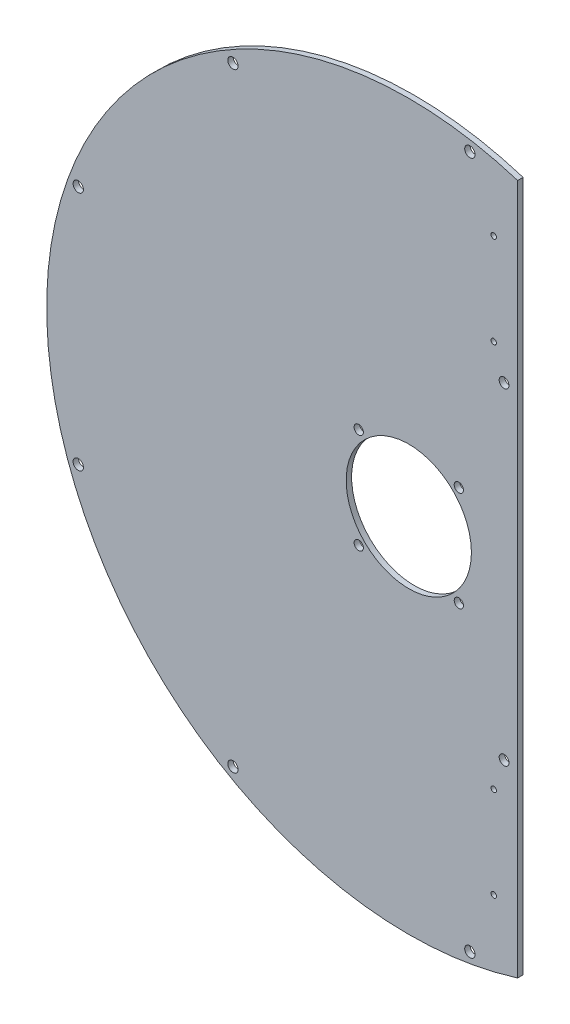
SolidWorks part; units mm, degrees
material "1.4301 (X5CrNi18-10)"
ref_plane "Ebene 1" through (0, 0, 0) normal (0, 0, 1) x (1, 0, 0)
ref_plane "Ebene 2" through (0, 0, 0) normal (0, 1, 0) x (1, 0, 0)
ref_plane "Ebene 3" through (0, 0, 0) normal (1, 0, 0) x (0, 0, -1)
sketch "Skizze1" plane through (0, 0, 0) normal (0, 0, 1) x (1, 0, 0)
  line L0 (100, 317.1061) -> (100, -317.1061)
  line L1 (0, 0) -> (0, 365.1695) construction
  line L2 (0, 0) -> (63.3988, 359.5525) construction
  line L3 (0, 0) -> (56.0884, 318.0929) construction
  line L4 (0, 0) -> (-194.2815, 336.5054) construction
  line L5 (0, 0) -> (68.873, -390.5983) construction
  arc A0 (100, 317.1061) -> (100, -317.1061) centre (0, 0) ccw
  circle A1 centre (56.0884, 318.0929) radius 4.75
  circle A2 centre (323, 0) radius 4.75 [skipped]
  circle A3 centre (247.4324, -207.6204) radius 4.75 [skipped]
  arc A4 (71.0884, 315.0801) -> (71.0884, -315.0801) centre (0, 0) ccw construction
  circle A5 centre (56.0884, -318.0929) radius 4.75
  circle A6 centre (-161.5, -279.7262) radius 4.75
  circle A7 centre (-303.5207, -110.4725) radius 4.75
  circle A8 centre (-303.5207, 110.4725) radius 4.75
  circle A9 centre (-161.5, 279.7262) radius 4.75
  circle A10 centre (247.4324, 207.6204) radius 4.75 [skipped]
  dimension "D1" = 665
  dimension "D3" = 9.5
  dimension "D8" = 646
  dimension "D6" = 200
  dimension "D2" = 100
  dimension "D4" = 40
  dimension "D5" = 10
  dimension "D7" = 323
  dimension "D9" = 15
extrude "Linear austragen1" add sketch "Skizze1" along normal blind 5
sketch "Skizze4" plane through (0, 0, 5) normal (0, 0, 1) x (1, 0, 0)
  line L1 (100, -317.1061) -> (100, 317.1061)
  line L2 (100, -317.1061) -> (100, 317.1061)
  arc A1 (100, 317.1061) -> (100, -317.1061) centre (0, 0) ccw
  arc A2 (100, 317.1061) -> (100, -317.1061) centre (0, 0) ccw
  dimension "D1" = 0
sketch "Skizze10" plane through (0, 0, 5) normal (0, 0, 1) x (1, 0, 0)
  circle A0 centre (0, 0) radius 57.5
  dimension "D1" = 115
extrude "Schnitt-Linear austragen3" cut sketch "Skizze10" against normal through all
sketch "Skizze15" plane through (0, 0, 5) normal (0, 0, 1) x (1, 0, 0)
  line L0 (0, 82.1456) -> (0, -86.7126) construction
  line L1 (-72.4332, 0) -> (68.4613, 0) construction
  line L2 (0, 0) -> (-71.1009, 71.1009) construction
  line L3 (0, 0) -> (71.1009, 71.1009) construction
  line L4 (0, 0) -> (71.1009, -71.1009) construction
  line L5 (0, 0) -> (-71.1009, -71.1009) construction
  circle A0 centre (-45.9619, 45.9619) radius 4.25
  circle A1 centre (45.9619, 45.9619) radius 4.25
  circle A2 centre (45.9619, -45.9619) radius 4.25
  circle A3 centre (-45.9619, -45.9619) radius 4.25
  circle A4 centre (0, 0) radius 65 construction
  dimension "D2" = 130
  dimension "D3" = 8.5
  dimension "D1" = 45
extrude "Schnitt-Linear austragen5" cut sketch "Skizze15" against normal through all
hole_wizard "M6 Gewindebohrung1" positions "Skizze18" profile "Skizze19" tap size "M6" standard "Gabler-Normteile" end condition through all
sketch "Skizze18" plane through (0, 0, 5) normal (0, 0, 1) x (1, 0, 0)
  line L0 (0, 0) -> (100, 0) construction
  line L1 (100, -317.1061) -> (100, 317.1061) construction
  point P0 (78, -262)
  point P3 (78, -178)
  point P6 (78, 178)
  point P9 (78, 262)
  point P24 (0, 0)
  point P25 (0, 0)
  point P26 (0, 0)
  dimension "D1" = 84
  dimension "D2" = 356
  dimension "D3" = 84
  dimension "D4" = 22
sketch "Skizze19" plane through (78, -262, 5) normal (1, 0, 0) x (0, -1, 0)
  line L0 (0, 0) -> (0, 5)
  line L1 (0, 5) -> (2.5, 5)
  line L2 (2.5, 5) -> (2.5, 0)
  line L5 (2.5, 0) -> (0, 0)
  line L11 (0, -6.35) -> (0, 107.95) construction
  dimension "Bohrerdurchmesser" = 5
  dimension "Bohrungstiefe" = 5
cosmetic thread "Bohrungsgewinde1" parameters "D2"=6
cosmetic thread "Bohrungsgewinde2" parameters "D2"=6
cosmetic thread "Bohrungsgewinde3" parameters "D2"=6
cosmetic thread "Bohrungsgewinde4" parameters "D2"=6
sketch "Skizze17" plane through (0, 0, 5) normal (0, 0, 1) x (1, 0, 0)
  line L0 (100, -317.1061) -> (100, 317.1061) construction
  circle A0 centre (87.5, -150) radius 4.5
  circle A1 centre (87.5, 150) radius 4.5
  circle A2 centre (0, 0) radius 57.5 construction
  dimension "D1" = 300
  dimension "D2" = 150
  dimension "D3" = 12.5
  dimension "D4" = 9
extrude "Schnitt-Linear austragen7" cut sketch "Skizze17" against normal through all
